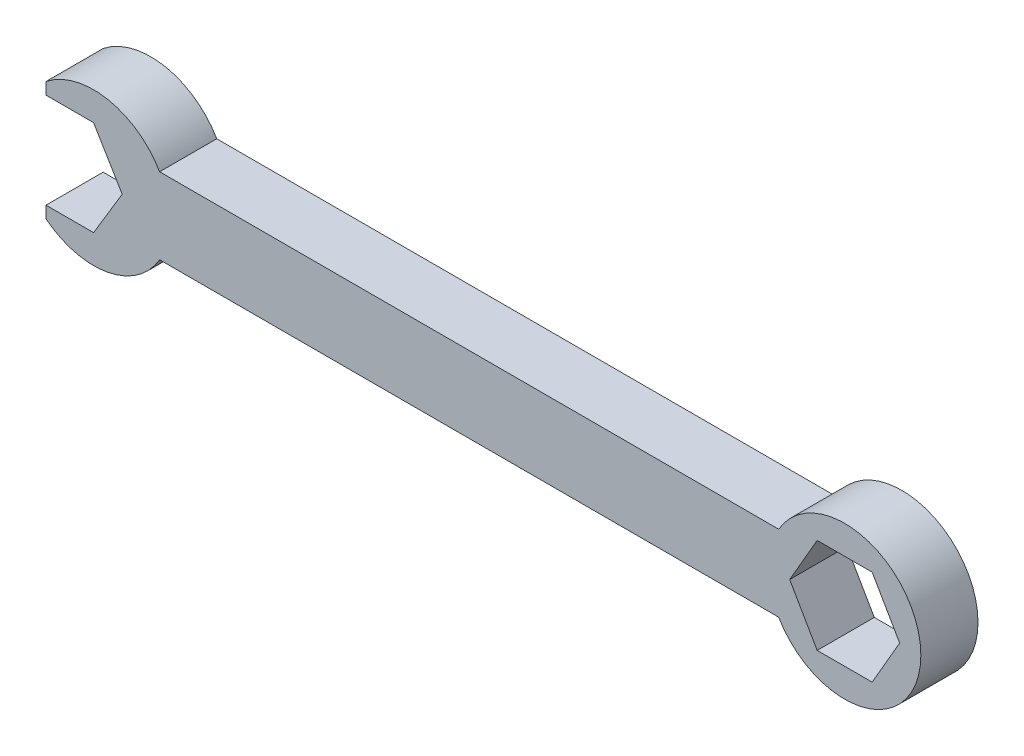
SolidWorks part; units mm, degrees
ref_plane "Płaszczyzna przednia" through (0, 0, 0) normal (0, 0, 1) x (1, 0, 0)
ref_plane "Płaszczyzna górna" through (0, 0, 0) normal (0, 1, 0) x (1, 0, 0)
ref_plane "Płaszczyzna prawa" through (0, 0, 0) normal (1, 0, 0) x (0, 0, -1)
sketch "Szkic2" plane through (0, 0, 0) normal (0, 0, 1) x (1, 0, 0)
  line L0 (0, 0) -> (105.1801, 0) construction
  line L1 (4.9888, 5.08) -> (87.5388, 5.08)
  line L2 (4.9888, -5.08) -> (87.5388, -5.08)
  line L3 (0, 0) -> (-3.81, 6.35)
  line L4 (-3.81, 6.35) -> (-10.16, 6.35)
  line L5 (0, 0) -> (-3.81, -6.35)
  line L6 (-3.81, -6.35) -> (-10.16, -6.35)
  line L7 (-10.16, 6.35) -> (-10.16, 7.9311)
  line L8 (-10.16, -6.35) -> (-10.16, -7.9311)
  line L9 (-3.81, 6.35) -> (-3.81, -6.35) construction
  line L11 (103.67, 0) -> (100.0038, 6.35)
  line L12 (100.0038, 6.35) -> (92.6715, 6.35)
  line L13 (92.6715, 6.35) -> (89.0053, 0)
  line L14 (89.0053, 0) -> (92.6715, -6.35)
  line L15 (92.6715, -6.35) -> (100.0038, -6.35)
  line L16 (100.0038, -6.35) -> (103.67, 0)
  arc A0 (-10.16, -7.9311) -> (-10.16, 7.9311) centre (-3.81, 0) ccw
  circle A1 centre (96.3376, 0) radius 10.16
  circle A2 centre (96.3376, 0) radius 6.35 construction
  dimension "D7" = 20.32
  dimension "D8" = 20.32
  dimension "D1" = 82.55
  dimension "D2" = 6.35
  dimension "D3" = 12.7
  dimension "D4" = 10.16
  dimension "D5" = 10.16
  dimension "D6" = 5.08
  dimension "D9" = 12.7
  dimension "D10" = 3.6662
extrude "Dodanie-wyciągnięcie2" add sketch "Szkic2" along normal blind 7.62 contours A0 L7 L4 L3 L5 L6 L8 | A1 L1 A0 L2 | A1 L16 L15 L14 L13 L12 L11
